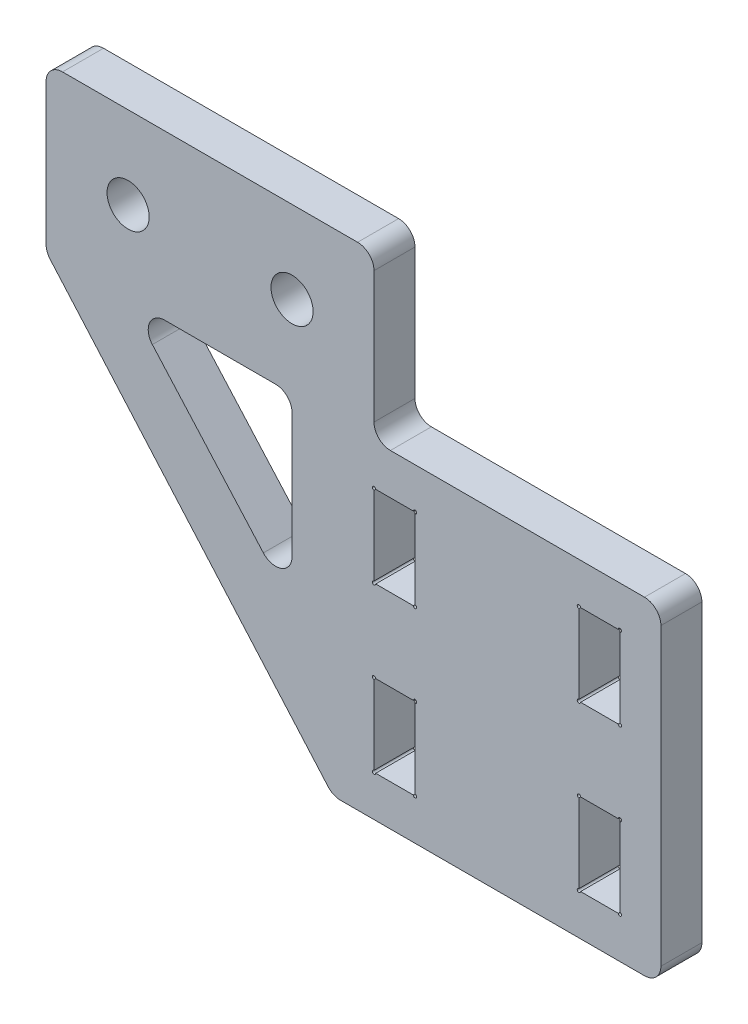
SolidWorks part; units mm, degrees
ref_plane "Front Plane" through (0, 0, 0) normal (0, 0, 1) x (1, 0, 0)
ref_plane "Top Plane" through (0, 0, 0) normal (0, 1, 0) x (1, 0, 0)
ref_plane "Right Plane" through (0, 0, 0) normal (1, 0, 0) x (0, 0, -1)
sketch "Sketch1" plane through (0, 0, 0) normal (0, 0, 1) x (1, 0, 0)
  line L0 (-38.1, 50.8) -> (-12.7, 50.8)
  line L1 (0, 0) -> (-6.35, 0)
  line L2 (0, 50.8) -> (0, 76.2)
  line L3 (0, 76.2) -> (-50.8, 76.2)
  line L4 (-50.8, 50.8) -> (-50.8, 76.2)
  line L5 (0, 0) -> (44.45, 0)
  line L6 (0, 6.61) -> (0, 18.79)
  line L7 (-12.7, 50.8) -> (-12.7, 22.225)
  line L8 (44.45, 0) -> (44.45, 32.01)
  line L9 (0.26, 44.45) -> (6.09, 44.45)
  line L10 (0, 44.19) -> (0, 32.01)
  line L11 (0.26, 31.75) -> (6.09, 31.75)
  line L12 (6.35, 44.19) -> (6.35, 32.01)
  line L13 (0.26, 19.05) -> (6.09, 19.05)
  line L14 (0, 18.79) -> (0, 6.61)
  line L15 (0.26, 6.35) -> (6.09, 6.35)
  line L16 (6.35, 18.79) -> (6.35, 6.61)
  line L17 (-50.8, 50.8) -> (-6.35, 0)
  line L18 (0, 32.01) -> (0, 44.45)
  line L19 (-38.1, 50.8) -> (-12.7, 22.225)
  line L20 (44.45, 44.19) -> (44.45, 50.8)
  line L21 (0, 50.8) -> (44.45, 50.8)
  line L22 (19.05, 0) -> (19.05, 50.8) construction
  line L23 (31.75, 18.79) -> (31.75, 6.61)
  line L24 (37.84, 6.35) -> (32.01, 6.35)
  line L25 (38.1, 18.79) -> (38.1, 6.61)
  line L26 (37.84, 19.05) -> (32.01, 19.05)
  line L27 (44.45, 44.19) -> (44.45, 32.01)
  line L28 (31.75, 44.45) -> (31.49, 44.45) construction
  line L29 (38.1, 32.01) -> (38.1, 44.45)
  line L30 (31.75, 44.19) -> (31.75, 32.01)
  line L31 (38.1, 6.61) -> (38.1, 18.79)
  line L32 (6.35, 44.45) -> (6.61, 44.45) construction
  line L33 (37.84, 31.75) -> (32.01, 31.75)
  line L34 (38.1, 44.19) -> (38.1, 32.01)
  line L35 (37.84, 44.45) -> (32.01, 44.45)
  arc A0 (0, 6.61) -> (0.26, 6.35) centre (0, 6.35) ccw
  arc A1 (0, 18.79) -> (0.26, 19.05) centre (0, 19.05) cw
  arc A2 (6.35, 6.61) -> (6.09, 6.35) centre (6.35, 6.35) cw
  arc A3 (6.35, 18.79) -> (6.09, 19.05) centre (6.35, 19.05) ccw
  arc A4 (6.35, 32.01) -> (6.09, 31.75) centre (6.35, 31.75) cw
  arc A5 (0, 32.01) -> (0.26, 31.75) centre (0, 31.75) ccw
  arc A6 (0, 44.19) -> (0.26, 44.45) centre (0, 44.45) cw
  arc A7 (6.35, 44.19) -> (6.09, 44.45) centre (6.35, 44.45) ccw
  arc A8 (31.75, 44.19) -> (32.01, 44.45) centre (31.75, 44.45) cw
  arc A9 (38.1, 44.19) -> (37.84, 44.45) centre (38.1, 44.45) ccw
  arc A10 (38.1, 32.01) -> (37.84, 31.75) centre (38.1, 31.75) cw
  arc A11 (31.75, 32.01) -> (32.01, 31.75) centre (31.75, 31.75) ccw
  arc A12 (31.75, 18.79) -> (32.01, 19.05) centre (31.75, 19.05) cw
  arc A13 (31.75, 6.61) -> (32.01, 6.35) centre (31.75, 6.35) ccw
  arc A14 (38.1, 18.79) -> (37.84, 19.05) centre (38.1, 19.05) ccw
  arc A15 (38.1, 6.61) -> (37.84, 6.35) centre (38.1, 6.35) cw
  dimension "D14" = 44.45
  dimension "D1" = 50.8
  dimension "D2" = 76.2
  dimension "D3" = 25.4
  dimension "D4" = 50.8
  dimension "D5" = 12.7
  dimension "D6" = 6.35
  dimension "D7" = 12.7
  dimension "D8" = 12.7
  dimension "D9" = 6.35
  dimension "D10" = 12.7
  dimension "D11" = 25.4
  dimension "D12" = 6.35
  dimension "D13" = 28.575
  dimension "D16" = 25.4
extrude "Boss-Extrude1" add sketch "Sketch1" along normal blind 6.35
fillet "Fillet1" radius 2.54 7 edges at (-50.8, 76.2, 3.175) (-50.8, 50.8, 3.175) (44.45, 0, 3.175) (-6.35, 0, 3.175) (44.45, 50.8, 3.175) (0, 50.8, 3.175) (0, 76.2, 3.175)
fillet "Fillet2" radius 2.54 3 edges at (-12.7, 22.225, 3.175) (-38.1, 50.8, 3.175) (-12.7, 50.8, 3.175)
hole_wizard "F (0.257) Diameter Hole1" positions "Sketch3" profile "Sketch2" hole size "F" standard "ANSI Inch" end condition through all
sketch "Sketch3" plane through (0, 0, 6.35) normal (0, 0, 1) x (1, 0, 0)
  point P8 (-38.1, 63.4475)
  point P10 (-12.7, 63.4475)
  dimension "D1" = 25.4
sketch "Sketch2" plane through (-38.1, 63.4475, 6.35) normal (1, 0, 0) x (0, -1, 0)
  line L0 (0, 0) -> (0, 6.35)
  line L1 (0, 6.35) -> (3.2639, 6.35)
  line L2 (3.2639, 6.35) -> (3.2639, 0)
  line L5 (3.2639, 0) -> (0, 0)
  line L11 (0, -6.35) -> (0, 107.95) construction
  dimension "Thru Hole Dia." = 6.5278
  dimension "Thru Hole Depth" = 6.35
